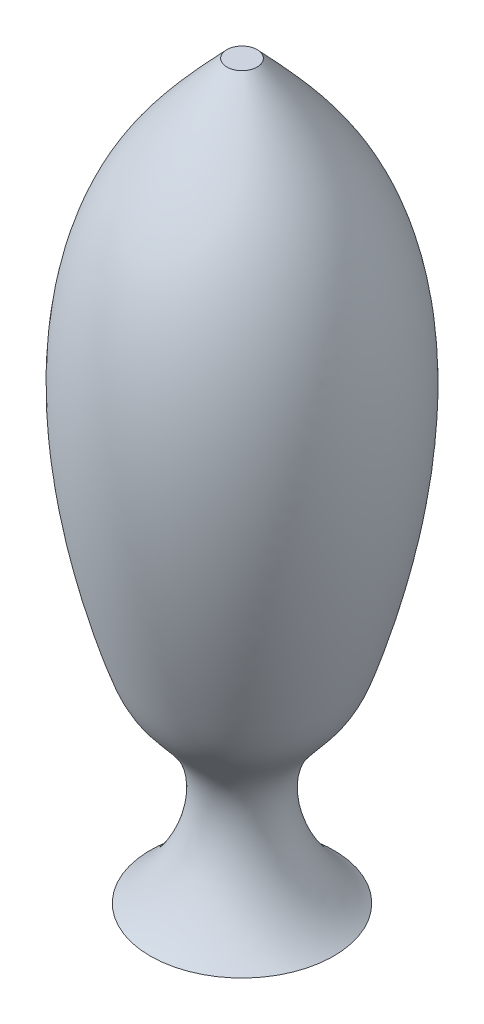
SolidWorks part; units mm, degrees
material "山毛榉"
ref_plane "前视基准面" through (0, 0, 0) normal (0, 0, 1) x (1, 0, 0)
ref_plane "上视基准面" through (0, 0, 0) normal (0, 1, 0) x (1, 0, 0)
ref_plane "右视基准面" through (0, 0, 0) normal (1, 0, 0) x (0, 0, -1)
sketch "草图1" plane through (0, 0, 0) normal (0, 1, 0) x (1, 0, 0)
  circle A0 centre (0, 0) radius 8
extrude "凸台-拉伸1" add sketch "草图1" along normal blind 40
sketch "草图2" plane through (0, 0, 0) normal (0, 0, 1) x (1, 0, 0)
  line L0 (0, 40) -> (0, 0) construction
  line L1 (8, 40) -> (-8, 40) construction
  line L2 (-8, 0) -> (8, 0) construction
  line L3 (-1.4967, 40.5671) -> (-0.8263, 40)
  spline S0 degree 3 poles (-0.8263, 40) (-2.3969, 38.3384) (-9.2386, 31.1004) (-7.6372, 18.4868) (-4.5418, 9.5023) (-0.8543, 6.3955) (-3.4922, -0.0104) (-21.6456, -5.4925) (-23.247, 42.3224) (-5.2772, 41.0352) (-2.438, 40.6836) (-1.4967, 40.5671) knots 0 0 0 0 0.069367 0.302167 0.328429 0.361708 0.440321 0.478739 0.910974 0.970486 1 1 1 1
revolve "切除-旋转1" cut sketch "草图2" angle 360 about L0
